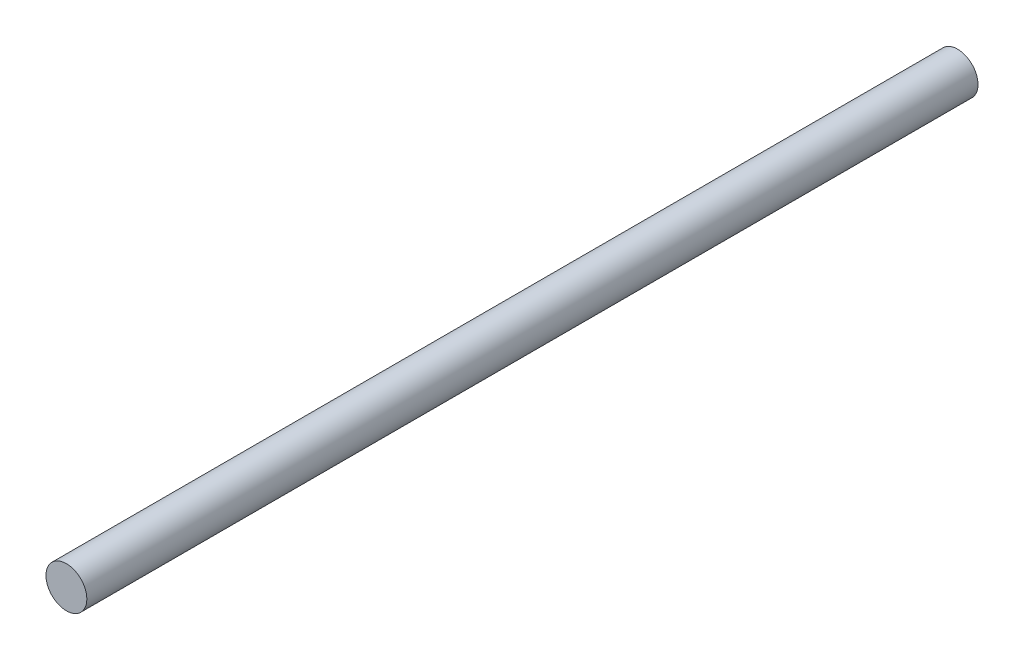
SolidWorks part; units mm, degrees
ref_plane "Front Plane" through (0, 0, 0) normal (0, 0, 1) x (1, 0, 0)
ref_plane "Top Plane" through (0, 0, 0) normal (0, 1, 0) x (1, 0, 0)
ref_plane "Right Plane" through (0, 0, 0) normal (1, 0, 0) x (0, 0, -1)
sketch "Sketch1" plane through (0, 0, 0) normal (0, 0, 1) x (1, 0, 0)
  circle A0 centre (0, 0) radius 5
extrude "Boss-Extrude1" add sketch "Sketch1" along normal blind 218
